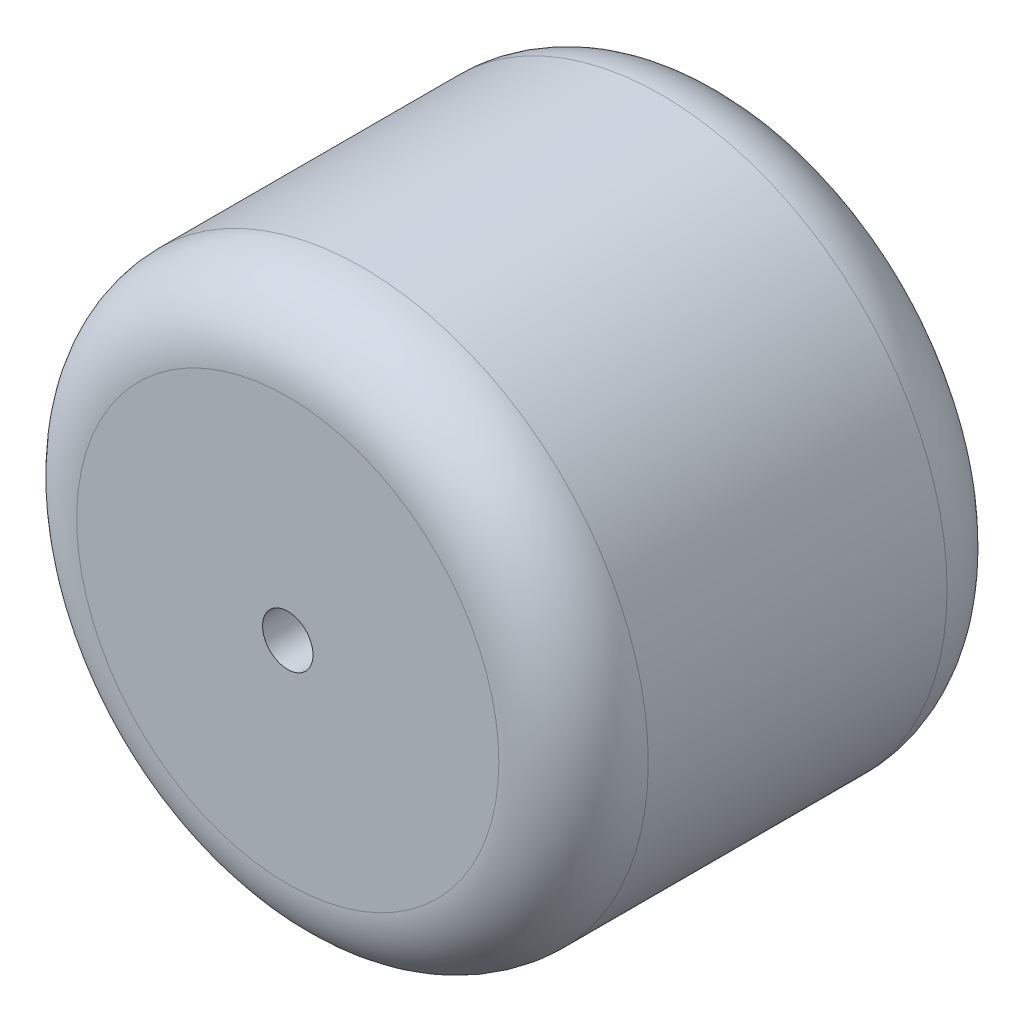
SolidWorks part; units mm, degrees
ref_plane "Front Plane" through (0, 0, 0) normal (0, 0, 1) x (1, 0, 0)
ref_plane "Top Plane" through (0, 0, 0) normal (0, 1, 0) x (1, 0, 0)
ref_plane "Right Plane" through (0, 0, 0) normal (1, 0, 0) x (0, 0, -1)
sketch "Sketch1" plane through (0, 0, 0) normal (0, 0, 1) x (1, 0, 0)
  circle A0 centre (0, 0) radius 7.65
  circle A1 centre (0, 0) radius 0.675
  dimension "D1" = 15.3
  dimension "D2" = 1.35
extrude "Boss-Extrude1" add sketch "Sketch1" along normal blind 12
fillet "Fillet1" radius 2 2 edges at (7.65, 0, 12) (7.65, 0, 0)
